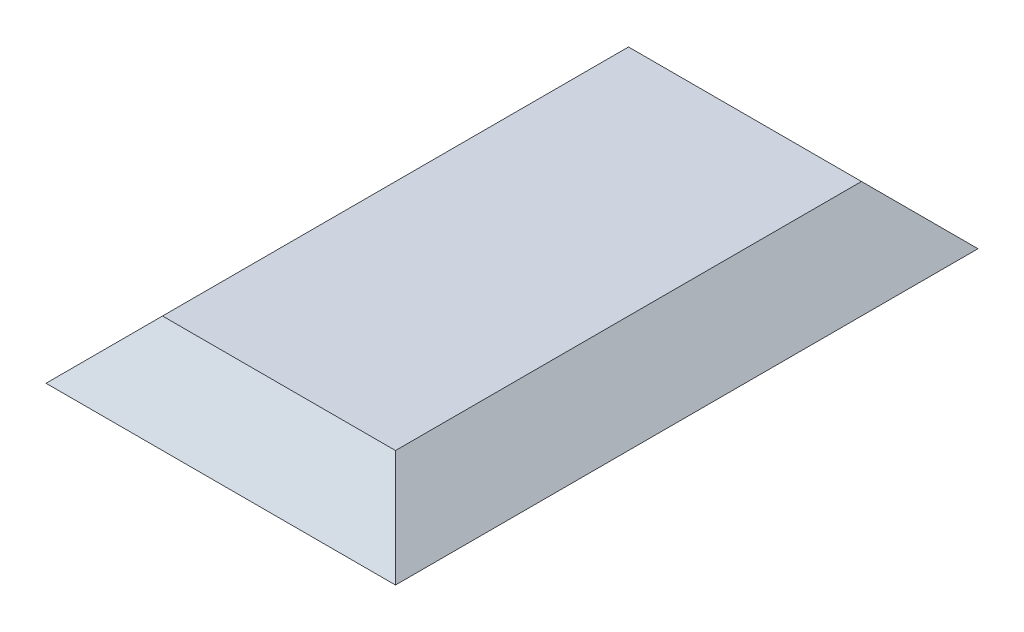
SolidWorks part; units mm, degrees
ref_plane "Frontal Plane" through (0, 0, 0) normal (0, 0, 1) x (1, 0, 0)
ref_plane "Horizontal Plane" through (0, 0, 0) normal (0, 1, 0) x (1, 0, 0)
ref_plane "Profile Plane" through (0, 0, 0) normal (1, 0, 0) x (0, 0, -1)
sketch "Sketch1" plane through (0, 0, 0) normal (0, 0, 1) x (1, 0, 0)
  line L0 (-228.6, 0) -> (228.6, 0)
  line L1 (-228.6, 0) -> (-152.4, 76.2)
  line L2 (-152.4, 76.2) -> (152.4, 76.2)
  line L3 (152.4, 76.2) -> (228.6, 0)
  point P3 (0, 0)
  dimension "D1" = 457.2
  dimension "D2" = 304.8
  dimension "D3" = 45
extrude "Boss-Extrude1" add sketch "Sketch1" along normal mid plane 762
sketch "Sketch2" plane through (0, 0, 0) normal (1, 0, 0) x (0, 0, -1)
  line L0 (-381, 0) -> (-381, 76.2)
  line L1 (-381, 0) -> (-381, 76.2) construction
  line L2 (-381, 76.2) -> (381, 76.2) construction
  line L3 (-381, 76.2) -> (-304.8, 76.2)
  line L4 (-304.8, 76.2) -> (-381, 0)
  line L5 (-381, 0) -> (381, 0) construction
  line L6 (381, 0) -> (381, 76.2)
  line L7 (381, 76.2) -> (304.8, 76.2)
  line L8 (304.8, 76.2) -> (381, 0)
  dimension "D1" = 45
  dimension "D2" = 45
extrude "Cut-Extrude1" cut sketch "Sketch2" against normal through all both and the other way through all
shell "Shell2" thickness 12.7
